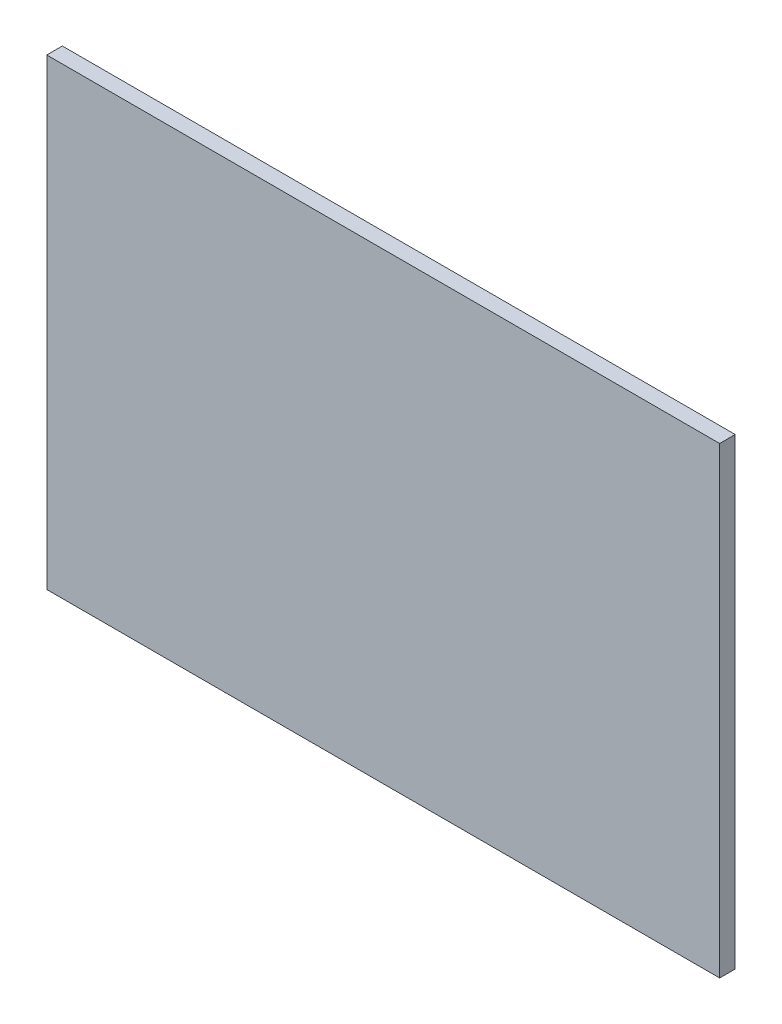
SolidWorks part; units mm, degrees
ref_plane "Front Plane" through (0, 0, 0) normal (0, 0, 1) x (1, 0, 0)
ref_plane "Top Plane" through (0, 0, 0) normal (0, 1, 0) x (1, 0, 0)
ref_plane "Right Plane" through (0, 0, 0) normal (1, 0, 0) x (0, 0, -1)
sketch "Sketch1" plane through (0, 0, 0) normal (0, 0, 1) x (1, 0, 0)
  line L0 (3783.3004, 1214.5414) -> (3783.3004, 1780.9614)
  line L1 (3783.3004, 1780.9614) -> (2959.9289, 1780.9614)
  line L2 (2959.9289, 1780.9614) -> (2959.9289, 1214.5414)
  line L3 (2959.9289, 1214.5414) -> (3783.3004, 1214.5414)
extrude "Boss-Extrude1" add sketch "Sketch1" along normal blind 19.05
